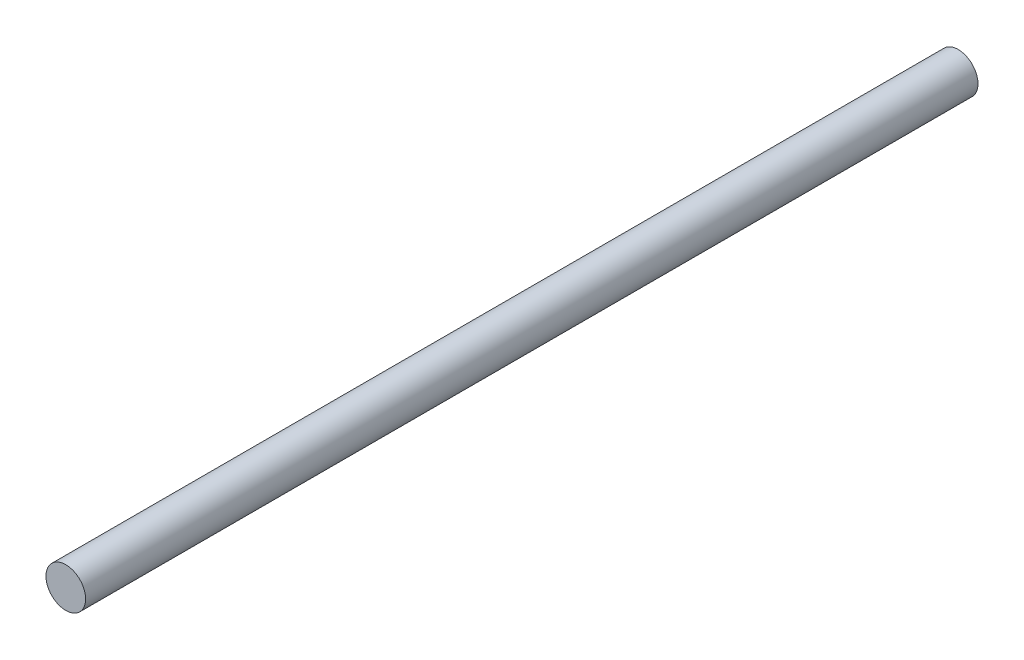
SolidWorks part; units mm, degrees
ref_plane "Front Plane" through (0, 0, 0) normal (0, 0, 1) x (1, 0, 0)
ref_plane "Top Plane" through (0, 0, 0) normal (0, 1, 0) x (1, 0, 0)
ref_plane "Right Plane" through (0, 0, 0) normal (1, 0, 0) x (0, 0, -1)
sketch "Sketch1" plane through (0, 0, 0) normal (0, 0, 1) x (1, 0, 0)
  circle A0 centre (0, 0) radius 30
  dimension "D1" = 60
extrude "Boss-Extrude1" add sketch "Sketch1" along normal blind 1350
